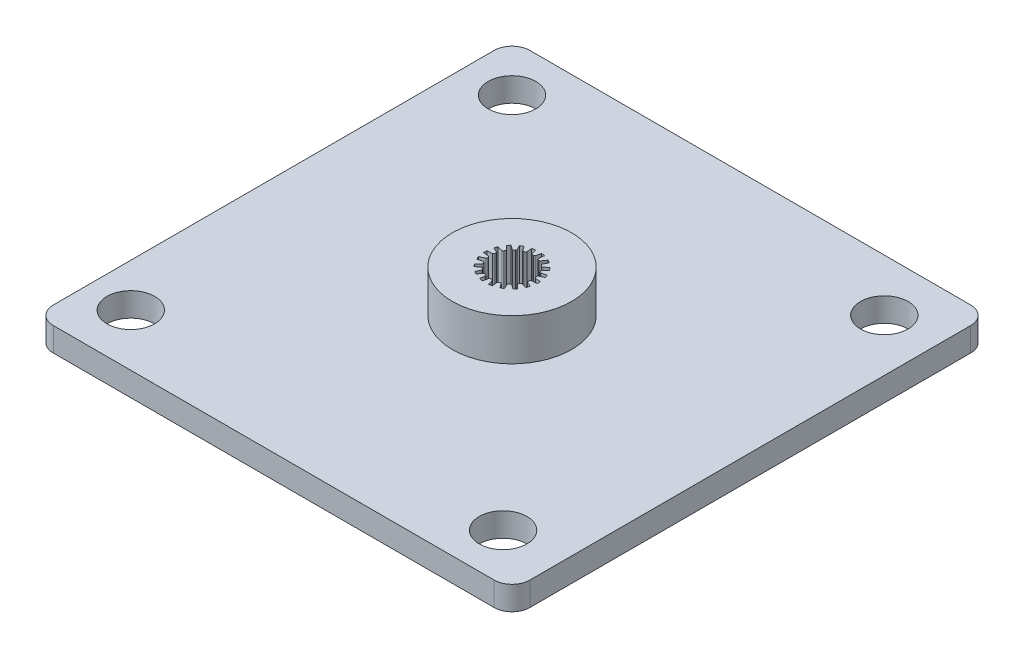
SolidWorks part; units mm, degrees
ref_plane "Front Plane" through (0, 0, 0) normal (0, 0, 1) x (1, 0, 0)
ref_plane "Top Plane" through (0, 0, 0) normal (0, 1, 0) x (1, 0, 0)
ref_plane "Right Plane" through (0, 0, 0) normal (1, 0, 0) x (0, 0, -1)
sketch "Sketch1" plane through (0, 0, 0) normal (0, 1, 0) x (1, 0, 0)
  line L1 (-20, -20) -> (20, -20)
  line L2 (-20, -20) -> (-20, 20)
  line L3 (-20, 20) -> (20, 20)
  line L4 (20, -20) -> (20, 20)
  line L5 (-20, -20) -> (20, 20) construction
  line L6 (-20, 20) -> (20, -20) construction
  circle A0 centre (-16, 16) radius 2
  circle A1 centre (15.6261, 15.6261) radius 2
  circle A2 centre (15.2521, -16) radius 2
  circle A3 centre (-16.3739, -15.6261) radius 2
  point P0 (0, 0)
  point P9 (-17.2488, 17.2488)
  point P16 (-0.3739, 0)
  dimension "D3" = 4
  dimension "D1" = 40
  dimension "D2" = 40
  dimension "D5" = 4
  dimension "D4" = 4
extrude "Boss-Extrude1" add sketch "Sketch1" along normal blind 2
fillet "Fillet1" radius 1.5 4 edges at (-20, 1, -20) (20, 1, -20) (20, 1, 20) (-20, 1, 20)
sketch "Sketch2" plane through (0, 2, 0) normal (0, 1, 0) x (1, 0, 0)
  circle A0 centre (0, 0) radius 5
  dimension "D1" = 10
extrude "Boss-Extrude2" add sketch "Sketch2" along normal blind 3.5
sketch "Sketch4" plane through (0, 5.5, 0) normal (0, 1, 0) x (1, 0, 0)
  line L1 (0.25, 2.2361) -> (0.1452, 1.8247)
  line L3 (-0.1452, 1.8247) -> (-0.25, 2.2361)
  line L4 (0.4877, 1.7643) -> (0.5299, 2.1867)
  line L5 (0.9997, 2.0157) -> (0.7605, 1.665)
  line L6 (1.0617, 1.4911) -> (1.2458, 1.8736)
  line L7 (1.6288, 1.5522) -> (1.2841, 1.3045)
  line L8 (1.5076, 1.0381) -> (1.8115, 1.3345)
  line L9 (2.0615, 0.9015) -> (1.6528, 0.7866)
  line L10 (1.7717, 0.4598) -> (2.1587, 0.6345)
  line L11 (2.2455, 0.1421) -> (1.8222, 0.1739)
  line L12 (1.8222, -0.1739) -> (2.2455, -0.1421)
  line L13 (2.1587, -0.6345) -> (1.7717, -0.4598)
  line L14 (1.6528, -0.7866) -> (2.0615, -0.9015)
  line L15 (1.8115, -1.3345) -> (1.5076, -1.0381)
  line L16 (1.2841, -1.3045) -> (1.6288, -1.5522)
  line L17 (1.2458, -1.8736) -> (1.0617, -1.4911)
  line L18 (0.7605, -1.665) -> (0.9997, -2.0157)
  line L19 (0.5299, -2.1867) -> (0.4877, -1.7643)
  line L20 (0.1452, -1.8247) -> (0.25, -2.2361)
  line L21 (-0.25, -2.2361) -> (-0.1452, -1.8247)
  line L22 (-0.4877, -1.7643) -> (-0.5299, -2.1867)
  line L23 (-0.9997, -2.0157) -> (-0.7605, -1.665)
  line L24 (-1.0617, -1.4911) -> (-1.2458, -1.8736)
  line L25 (-1.6288, -1.5522) -> (-1.2841, -1.3045)
  line L26 (-1.5076, -1.0381) -> (-1.8115, -1.3345)
  line L27 (-2.0615, -0.9015) -> (-1.6528, -0.7866)
  line L28 (-1.7717, -0.4598) -> (-2.1587, -0.6345)
  line L29 (-2.2455, -0.1421) -> (-1.8222, -0.1739)
  line L30 (-1.8222, 0.1739) -> (-2.2455, 0.1421)
  line L31 (-2.1587, 0.6345) -> (-1.7717, 0.4598)
  line L32 (-1.6528, 0.7866) -> (-2.0615, 0.9015)
  line L33 (-1.8115, 1.3345) -> (-1.5076, 1.0381)
  line L34 (-1.2841, 1.3045) -> (-1.6288, 1.5522)
  line L35 (-1.2458, 1.8736) -> (-1.0617, 1.4911)
  line L36 (-0.7605, 1.665) -> (-0.9997, 2.0157)
  line L37 (-0.5299, 2.1867) -> (-0.4877, 1.7643)
  arc A0 (-0.9997, 2.0157) -> (-1.2458, 1.8736) centre (0, 0) ccw
  arc A1 (-0.5554, 1.6595) -> (-0.6412, 1.6283) centre (0, 0) ccw
  arc A2 (0.0457, 1.7494) -> (0.1452, 1.8247) centre (0.0483, 1.8494) ccw
  arc A3 (-0.0457, 1.7494) -> (-0.1452, 1.8247) centre (-0.0483, 1.8494) cw
  arc A4 (0.5554, 1.6595) -> (0.4877, 1.7643) centre (0.5872, 1.7543) cw
  arc A5 (0.6412, 1.6283) -> (0.7605, 1.665) centre (0.6779, 1.7213) ccw
  arc A6 (1.0895, 1.3695) -> (1.0617, 1.4911) centre (1.1518, 1.4477) cw
  arc A7 (1.1595, 1.3108) -> (1.2841, 1.3045) centre (1.2257, 1.3857) ccw
  arc A8 (1.4922, 0.9142) -> (1.5076, 1.0381) centre (1.5775, 0.9665) cw
  arc A9 (1.5379, 0.8352) -> (1.6528, 0.7866) centre (1.6257, 0.8829) ccw
  arc A10 (1.7149, 0.3487) -> (1.7717, 0.4598) centre (1.8129, 0.3687) cw
  arc A11 (1.7308, 0.2588) -> (1.8222, 0.1739) centre (1.8297, 0.2736) ccw
  arc A12 (1.7308, -0.2588) -> (1.8222, -0.1739) centre (1.8297, -0.2736) cw
  arc A13 (1.7149, -0.3487) -> (1.7717, -0.4598) centre (1.8129, -0.3687) ccw
  arc A14 (1.5379, -0.8352) -> (1.6528, -0.7866) centre (1.6257, -0.8829) cw
  arc A15 (1.4922, -0.9142) -> (1.5076, -1.0381) centre (1.5775, -0.9665) ccw
  arc A16 (1.1595, -1.3108) -> (1.2841, -1.3045) centre (1.2257, -1.3857) cw
  arc A17 (1.0895, -1.3695) -> (1.0617, -1.4911) centre (1.1518, -1.4477) ccw
  arc A18 (0.6412, -1.6283) -> (0.7605, -1.665) centre (0.6779, -1.7213) cw
  arc A19 (0.5554, -1.6595) -> (0.4877, -1.7643) centre (0.5872, -1.7543) ccw
  arc A20 (0.0457, -1.7494) -> (0.1452, -1.8247) centre (0.0483, -1.8494) cw
  arc A21 (-0.0457, -1.7494) -> (-0.1452, -1.8247) centre (-0.0483, -1.8494) ccw
  arc A22 (-0.5554, -1.6595) -> (-0.4877, -1.7643) centre (-0.5872, -1.7543) cw
  arc A23 (-0.6412, -1.6283) -> (-0.7605, -1.665) centre (-0.6779, -1.7213) ccw
  arc A24 (-1.0895, -1.3695) -> (-1.0617, -1.4911) centre (-1.1518, -1.4477) cw
  arc A25 (-1.1595, -1.3108) -> (-1.2841, -1.3045) centre (-1.2257, -1.3857) ccw
  arc A26 (-1.4922, -0.9142) -> (-1.5076, -1.0381) centre (-1.5775, -0.9665) cw
  arc A27 (-1.5379, -0.8352) -> (-1.6528, -0.7866) centre (-1.6257, -0.8829) ccw
  arc A28 (-1.7149, -0.3487) -> (-1.7717, -0.4598) centre (-1.8129, -0.3687) cw
  arc A29 (-1.7308, -0.2588) -> (-1.8222, -0.1739) centre (-1.8297, -0.2736) ccw
  arc A30 (-1.7308, 0.2588) -> (-1.8222, 0.1739) centre (-1.8297, 0.2736) cw
  arc A31 (-1.7149, 0.3487) -> (-1.7717, 0.4598) centre (-1.8129, 0.3687) ccw
  arc A32 (-1.5379, 0.8352) -> (-1.6528, 0.7866) centre (-1.6257, 0.8829) cw
  arc A33 (-1.4922, 0.9142) -> (-1.5076, 1.0381) centre (-1.5775, 0.9665) ccw
  arc A34 (-1.1595, 1.3108) -> (-1.2841, 1.3045) centre (-1.2257, 1.3857) cw
  arc A35 (-1.0895, 1.3695) -> (-1.0617, 1.4911) centre (-1.1518, 1.4477) ccw
  arc A36 (-0.6412, 1.6283) -> (-0.7605, 1.665) centre (-0.6779, 1.7213) cw
  arc A37 (-0.5554, 1.6595) -> (-0.4877, 1.7643) centre (-0.5872, 1.7543) ccw
  arc A38 (0.0457, 1.7494) -> (-0.0457, 1.7494) centre (0, 0) ccw
  arc A39 (0.6412, 1.6283) -> (0.5554, 1.6595) centre (0, 0) ccw
  arc A40 (1.1595, 1.3108) -> (1.0895, 1.3695) centre (0, 0) ccw
  arc A41 (1.5379, 0.8352) -> (1.4922, 0.9142) centre (0, 0) ccw
  arc A42 (1.7308, 0.2588) -> (1.7149, 0.3487) centre (0, 0) ccw
  arc A43 (-1.0895, 1.3695) -> (-1.1595, 1.3108) centre (0, 0) ccw
  arc A44 (-1.4922, 0.9142) -> (-1.5379, 0.8352) centre (0, 0) ccw
  arc A45 (-1.7149, 0.3487) -> (-1.7308, 0.2588) centre (0, 0) ccw
  arc A46 (-1.7308, -0.2588) -> (-1.7149, -0.3487) centre (0, 0) ccw
  arc A47 (-1.5379, -0.8352) -> (-1.4922, -0.9142) centre (0, 0) ccw
  arc A48 (-1.1595, -1.3108) -> (-1.0895, -1.3695) centre (0, 0) ccw
  arc A49 (-0.6412, -1.6283) -> (-0.5554, -1.6595) centre (0, 0) ccw
  arc A50 (-0.0457, -1.7494) -> (0.0457, -1.7494) centre (0, 0) ccw
  arc A51 (0.5554, -1.6595) -> (0.6412, -1.6283) centre (0, 0) ccw
  arc A52 (1.0895, -1.3695) -> (1.1595, -1.3108) centre (0, 0) ccw
  arc A53 (1.7149, -0.3487) -> (1.7308, -0.2588) centre (0, 0) ccw
  arc A54 (-0.25, 2.2361) -> (-0.5299, 2.1867) centre (0, 0) ccw
  arc A55 (0.5299, 2.1867) -> (0.25, 2.2361) centre (0, 0) ccw
  arc A56 (1.2458, 1.8736) -> (0.9997, 2.0157) centre (0, 0) ccw
  arc A57 (1.8115, 1.3345) -> (1.6288, 1.5522) centre (0, 0) ccw
  arc A58 (2.1587, 0.6345) -> (2.0615, 0.9015) centre (0, 0) ccw
  arc A59 (2.2455, -0.1421) -> (2.2455, 0.1421) centre (0, 0) ccw
  arc A60 (2.0615, -0.9015) -> (2.1587, -0.6345) centre (0, 0) ccw
  arc A61 (1.6288, -1.5522) -> (1.8115, -1.3345) centre (0, 0) ccw
  arc A62 (0.9997, -2.0157) -> (1.2458, -1.8736) centre (0, 0) ccw
  arc A63 (0.25, -2.2361) -> (0.5299, -2.1867) centre (0, 0) ccw
  arc A64 (-0.5299, -2.1867) -> (-0.25, -2.2361) centre (0, 0) ccw
  arc A65 (-1.2458, -1.8736) -> (-0.9997, -2.0157) centre (0, 0) ccw
  arc A66 (-1.8115, -1.3345) -> (-1.6288, -1.5522) centre (0, 0) ccw
  arc A67 (-2.1587, -0.6345) -> (-2.0615, -0.9015) centre (0, 0) ccw
  arc A68 (-2.2455, 0.1421) -> (-2.2455, -0.1421) centre (0, 0) ccw
  arc A69 (-2.0615, 0.9015) -> (-2.1587, 0.6345) centre (0, 0) ccw
  arc A70 (-1.6288, 1.5522) -> (-1.8115, 1.3345) centre (0, 0) ccw
  arc A71 (1.4922, -0.9142) -> (1.5379, -0.8352) centre (0, 0) ccw
  point P7 (0, 2.2361)
  point P151 (0, 0)
  dimension "D1" = 3.5
  dimension "D2" = 4.5
  dimension "D5" = 0.1
  dimension "D3" = 0.5
  dimension "D4" = 18
extrude "Cut-Extrude4" cut sketch "Sketch4" against normal blind 3 contours L34 A70 L33 A33 A44 A32 L32 A69 L31 A31 A45 A30 L30 A68 L29 A29 A46 A28 L28 A67 L27 A27 A47 A26 L26 A66 L25 A25 A48 A24 L24 A65 L23 A23 A49 A22 L22 A64 L21 A21 A50 A20 L20 A63 L19 A19 A51 A18 L18 A62 L17
